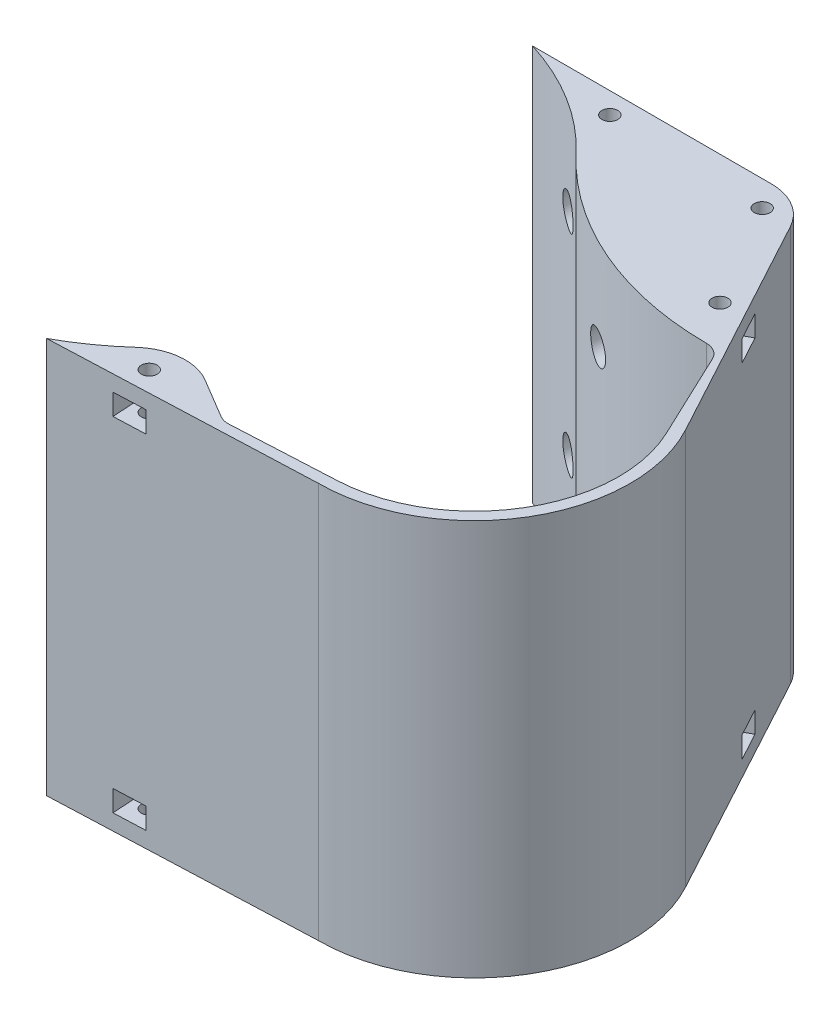
SolidWorks part; units mm, degrees
ref_plane "前视基准面" through (0, 0, 0) normal (0, 0, 1) x (1, 0, 0)
ref_plane "上视基准面" through (0, 0, 0) normal (0, 1, 0) x (1, 0, 0)
ref_plane "右视基准面" through (0, 0, 0) normal (1, 0, 0) x (0, 0, -1)
sketch "Sketch1" plane through (0, 0, 0) normal (0, 1, 0) x (1, 0, 0)
  line L0 (56.5917, 15.211) -> (88.688, 15.211)
  line L1 (68.764, 47.5) -> (77.559, 42.259) construction
  line L2 (99.6752, -3.32) -> (91.8515, 13.2084)
  line L3 (73.8831, 46.0904) -> (71.8355, 42.6542) construction
  line L4 (25.4653, -46.4814) -> (75, -44.5)
  line L5 (23.5106, 47.5) -> (68.764, 47.5)
  line L6 (77.559, 42.259) -> (100.9453, -0.9611)
  line L7 (56.7698, -43.2641) -> (76.389, -42.2646)
  line L8 (40.46, -34.2343) -> (54.8007, -42.7757)
  line L9 (25.4653, -46.4814) -> (40.4533, -45.8819) construction
  line L10 (40.4533, -45.8819) -> (40.2934, -41.8851) construction
  line L11 (46.1373, 47.5) -> (46.1373, 43.5) construction
  line L12 (46.1373, 43.5) -> (42.1373, 43.5) construction
  line L13 (89.2522, 20.6489) -> (85.7342, 18.7454) construction
  line L14 (85.7342, 18.7454) -> (83.3547, 23.1429) construction
  arc A2 (75, -44.5) -> (100.9453, -0.9611) centre (75, -15) ccw
  arc A4 (77.559, 42.259) -> (68.764, 47.5) centre (68.764, 37.5) ccw
  arc A13 (25.4653, -46.4814) -> (40.46, -34.2343) centre (0, 0) ccw
  arc A14 (91.8515, 13.2084) -> (88.688, 15.211) centre (88.688, 11.711) ccw
  arc A16 (76.389, -42.2646) -> (99.6752, -3.32) centre (75, -15) ccw
  arc A17 (54.8007, -42.7757) -> (56.7698, -43.2641) centre (56.5917, -39.7686) ccw
  arc A18 (23.5106, 47.5) -> (56.5917, 15.211) centre (8.4664, -1.004) cw
  circle A19 centre (71.8355, 42.6542) radius 1.5
  circle A20 centre (40.2934, -41.8851) radius 1.5
  circle A21 centre (42.1373, 43.5) radius 1.5
  circle A22 centre (83.3547, 23.1429) radius 1.5
  dimension "D1" = 3
  dimension "D4" = 4
  dimension "D6" = 4
  dimension "D7" = 10
  dimension "D8" = 4
  dimension "D9" = 3
  dimension "D10" = 5
  dimension "D11" = 4
  dimension "D12" = 3
  dimension "D2" = 4
  dimension "D5" = 3
  dimension "D3" = 15
extrude "Boss-Extrude1" add sketch "Sketch1" along normal blind 75
fillet "Fillet1" radius 60 1 edges at (56.5917, 37.5, -15.211)
fillet "Fillet2" radius 10 1 edges at (40.46, 37.5, 34.2343)
ref_plane "Plane1" through (0, 72, 0) normal (0, 1, 0) x (1, 0, 0)
sketch "Sketch3" plane through (0, 72, 0) normal (0, 1, 0) x (1, 0, 0)
  line L0 (39.1373, 43.5) -> (39.1373, 48.9141)
  line L1 (39.1373, 48.9141) -> (45.1373, 48.9141)
  line L2 (45.1373, 48.9141) -> (45.1373, 43.5)
  line L3 (68.764, 37.5) -> (71.8355, 42.6542) construction
  line L4 (74.4126, 41.1185) -> (77.2723, 45.9173)
  line L5 (74.4126, 41.1185) -> (69.2584, 44.19) construction
  line L6 (69.2584, 44.19) -> (72.118, 48.9887)
  line L7 (72.118, 48.9887) -> (77.2723, 45.9173)
  line L10 (81.9367, 25.7866) -> (87.4215, 28.7283)
  line L11 (84.7726, 20.4991) -> (90.2574, 23.4408)
  line L12 (90.2574, 23.4408) -> (87.4215, 28.7283)
  line L14 (37.2987, -42.0627) -> (37.6123, -47.3483)
  line L15 (43.2882, -41.7074) -> (43.6018, -46.9929)
  line L16 (43.6018, -46.9929) -> (37.6123, -47.3483)
  arc A0 (39.1373, 43.5) -> (45.1373, 43.5) centre (42.1373, 43.5) ccw
  arc A1 (69.2584, 44.19) -> (74.4126, 41.1185) centre (71.8355, 42.6542) ccw
  arc A2 (81.9367, 25.7866) -> (84.7726, 20.4991) centre (83.3547, 23.1429) ccw
  arc A3 (43.2882, -41.7074) -> (37.2987, -42.0627) centre (40.2934, -41.8851) ccw
  point P18 (83.3547, 23.1429)
  point P23 (40.2934, -41.8851)
  point P24 (40.2934, -41.8851)
  dimension "D1" = 6
  dimension "D2" = 6
  dimension "D3" = 6
  dimension "D4" = 6
extrude "Cut-Extrude1" cut sketch "Sketch3" against normal blind 4
ref_plane "Plane2" through (0, 37.5, 0) normal (0, 1, 0) x (1, 0, 0)
mirror "Mirror1" about plane through (0, 37.5, 0) normal (0, 1, 0) of "Cut-Extrude1"
sketch "Sketch4" plane through (0, 0, -47.5) normal (0, 0, -1) x (-1, 0, 0)
  line L0 (-23.5106, 37.5) -> (-36.5106, 37.5) construction
  line L1 (-23.5106, 75) -> (-23.5106, 0) construction
  line L2 (-36.5106, 37.5) -> (-36.5106, 57.5) construction
  line L3 (-36.5106, 57.5) -> (-61.5106, 57.5) construction
  circle A0 centre (-61.5106, 57.5) radius 2.9
  circle A1 centre (-36.5106, 57.5) radius 2.9
  circle A2 centre (-36.5106, 17.5) radius 2.9
  circle A3 centre (-61.5106, 17.5) radius 2.9
  dimension "D4" = 5.8
  dimension "D5" = 5.8
  dimension "D1" = 13
  dimension "D2" = 20
  dimension "D3" = 25
extrude "Cut-Extrude2" cut sketch "Sketch4" against normal blind 30
